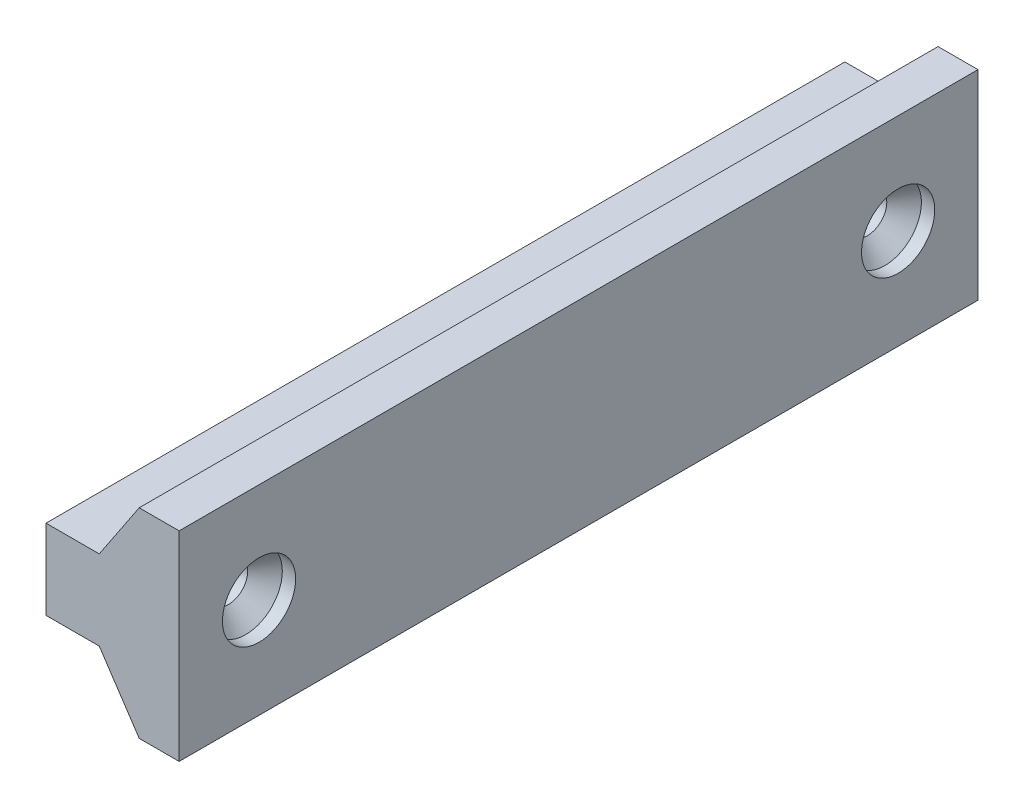
SolidWorks part; units mm, degrees
ref_plane "Спереди" through (0, 0, 0) normal (0, 0, 1) x (1, 0, 0)
ref_plane "Сверху" through (0, 0, 0) normal (0, 1, 0) x (1, 0, 0)
ref_plane "Справа" through (0, 0, 0) normal (1, 0, 0) x (0, 0, -1)
sketch "Эскиз1" plane through (0, 0, 0) normal (0, 0, 1) x (1, 0, 0)
  line L0 (-50.1214, 0) -> (63.6433, 0) construction
  line L1 (-10, -3) -> (-10, 3)
  line L2 (-10, 3) -> (-6, 3)
  line L3 (-6, 3) -> (-3, 7.5)
  line L4 (-3, 7.5) -> (0, 7.5)
  line L5 (0, 7.5) -> (0, -7.5)
  line L6 (-3, -7.5) -> (0, -7.5)
  line L7 (-6, -3) -> (-3, -7.5)
  line L8 (-10, -3) -> (-6, -3)
  point P10 (0, 0)
  point P13 (-10, 0)
  dimension "D1" = 6
  dimension "D2" = 10
  dimension "D3" = 4
  dimension "D4" = 15
  dimension "D5" = 3
extrude "Бобышка-Вытянуть1" add sketch "Эскиз1" along normal mid plane 60
sketch "Эскиз5" plane through (0, 0, 0) normal (1, 0, 0) x (0, 0, -1)
  line L0 (-30, -7.5) -> (-30, 7.5) construction
  line L1 (30, -7.5) -> (30, 7.5) construction
  circle A0 centre (-24, 0) radius 2.75
  circle A1 centre (24, 0) radius 2.75
  point P2 (0, 0)
  dimension "D1" = 5.5
  dimension "D2" = 6
  dimension "D3" = 6
extrude "Вырез-Вытянуть1" cut sketch "Эскиз5" against normal blind 1
hole_wizard "Зенковка для винта с потайной головкой M2.52" positions "Эскиз6" profile "Эскиз7" countersink size "M2.5" standard "DIN" end condition through all
sketch "Эскиз6" plane through (-1, 0, 0) normal (1, 0, 0) x (0, 0, -1)
  point P0 (-24, 0)
  point P4 (24, 0)
sketch "Эскиз7" plane through (-1, 0, 24) normal (0, 1, 0) x (0, 0, -1)
  line L0 (0, 0) -> (0, 9)
  line L1 (0, 9) -> (1.45, 9)
  line L2 (1.45, 9) -> (1.45, 1.3)
  line L3 (1.45, 1.3) -> (2.75, 0)
  line L5 (2.75, 0) -> (0, 0)
  line L6 (-1.45, 1.3) -> (-2.75, 0) construction
  line L11 (0, -6.35) -> (0, 107.95) construction
  dimension "Диаметр сквозного отверстия" = 2.9
  dimension "Глубина сквозного отверстия" = 9
  dimension "Диаметр передней зенковки" = 5.5
  dimension "Угол передней зенковки" = 90
